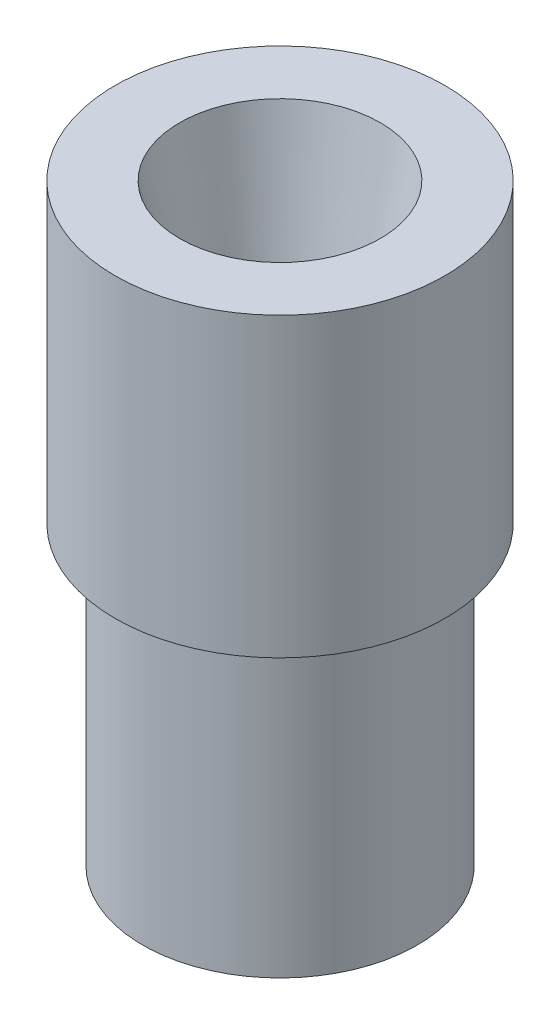
SolidWorks part; units mm, degrees
ref_plane "Front Plane" through (0, 0, 0) normal (0, 0, 1) x (1, 0, 0)
ref_plane "Top Plane" through (0, 0, 0) normal (0, 1, 0) x (1, 0, 0)
ref_plane "Right Plane" through (0, 0, 0) normal (1, 0, 0) x (0, 0, -1)
sketch "Sketch1" plane through (0, 0, 0) normal (0, 0, 1) x (1, 0, 0)
  line L0 (0, 0) -> (0, 20) construction
  line L1 (0, 20) -> (5.5562, 20)
  line L2 (5.5562, 20) -> (5.5562, 10)
  line L3 (5.5562, 10) -> (4.625, 10)
  line L4 (4.625, 10) -> (4.625, 0)
  line L5 (4.625, 0) -> (0, 0)
  line L6 (0, 0) -> (0, 20)
  dimension "D1" = 11.1125
  dimension "D2" = 9.25
  dimension "D3" = 10
  dimension "D4" = 10
revolve "Revolve1" add sketch "Sketch1" angle 360 about L0
sketch "Sketch2" plane through (0, 20, 0) normal (0, 1, 0) x (1, 0, 0)
  circle A0 centre (0, 0) radius 2.5
  dimension "D1" = 5
extrude "Cut-Extrude1" cut sketch "Sketch2" against normal blind 5
draft "Draft1" type of draft neutral plane draft angle 10 faces to draft 1 face at (0, 15, 2.5) neutral plane through (0, 15, 0) neutral plane normal (0, 1, 0) parameters "D1"=10
